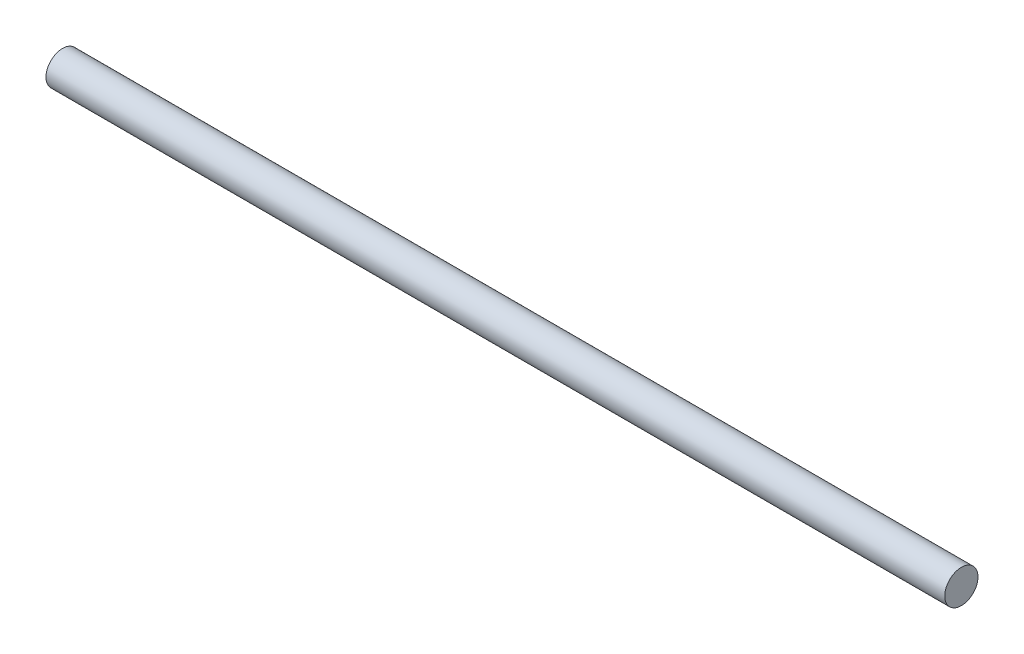
SolidWorks part; units mm, degrees
ref_plane "Front Plane" through (0, 0, 0) normal (0, 0, 1) x (1, 0, 0)
ref_plane "Top Plane" through (0, 0, 0) normal (0, 1, 0) x (1, 0, 0)
ref_plane "Right Plane" through (0, 0, 0) normal (1, 0, 0) x (0, 0, -1)
sketch "Sketch1" plane through (0, 0, 0) normal (1, 0, 0) x (0, 0, -1)
  circle A0 centre (0, 0) radius 11.1
extrude "Boss-Extrude1" add sketch "Sketch1" along normal mid plane 600
